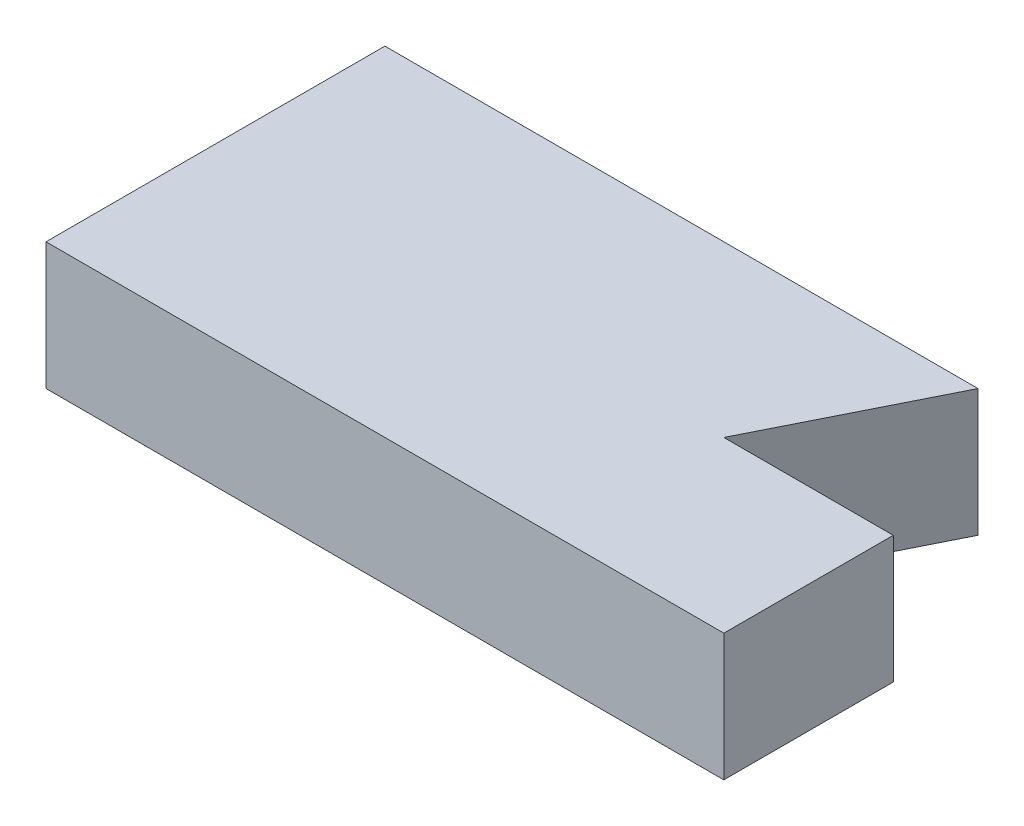
SolidWorks part; units mm, degrees
ref_plane "Front Plane" through (0, 0, 0) normal (0, 0, 1) x (1, 0, 0)
ref_plane "Top Plane" through (0, 0, 0) normal (0, 1, 0) x (1, 0, 0)
ref_plane "Right Plane" through (0, 0, 0) normal (1, 0, 0) x (0, 0, -1)
sketch "Sketch1" plane through (0, 0, 0) normal (0, 1, 0) x (1, 0, 0)
  line L0 (0, 0) -> (80, 0)
  line L1 (80, 0) -> (80, 20)
  line L2 (80, 20) -> (60, 20)
  line L3 (60, 20) -> (70, 40)
  line L4 (70, 40) -> (0, 40)
  line L5 (0, 40) -> (0, 0)
extrude "Boss-Extrude1" add sketch "Sketch1" along normal blind 15
